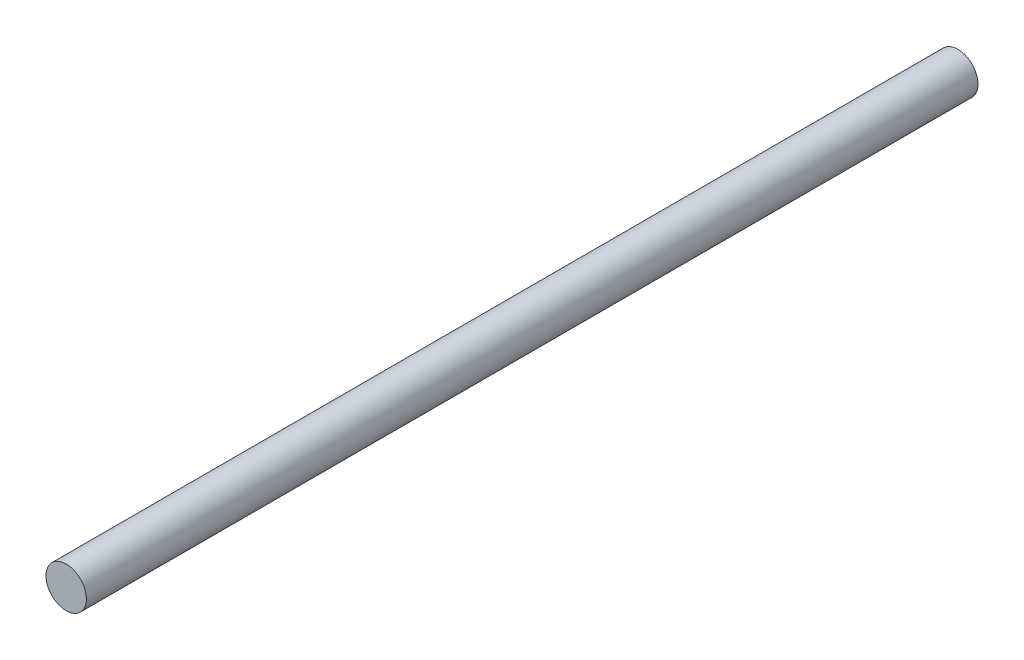
SolidWorks part; units mm, degrees
ref_plane "Front Plane" through (0, 0, 0) normal (0, 0, 1) x (1, 0, 0)
ref_plane "Top Plane" through (0, 0, 0) normal (0, 1, 0) x (1, 0, 0)
ref_plane "Right Plane" through (0, 0, 0) normal (1, 0, 0) x (0, 0, -1)
sketch "Sketch1" plane through (0, 0, 0) normal (0, 0, 1) x (1, 0, 0)
  circle A0 centre (0, 0) radius 2.159
extrude "Boss-Extrude1" add sketch "Sketch1" along normal blind 95.25
